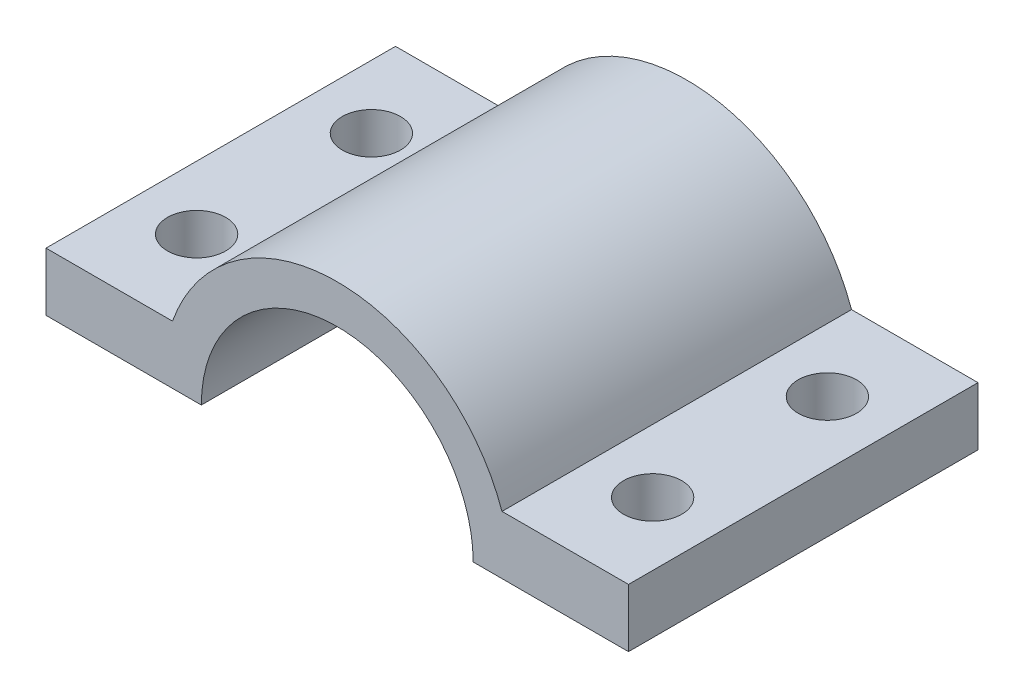
SolidWorks part; units mm, degrees
ref_plane "前视基准面" through (0, 0, 0) normal (0, 0, 1) x (1, 0, 0)
ref_plane "上视基准面" through (0, 0, 0) normal (0, 1, 0) x (1, 0, 0)
ref_plane "右视基准面" through (0, 0, 0) normal (1, 0, 0) x (0, 0, -1)
sketch "草图1" plane through (0, 0, 0) normal (0, 0, 1) x (1, 0, 0)
  line L0 (0, 0) -> (8, 0)
  line L1 (30, 0) -> (30, 3)
  line L2 (30, 3) -> (23.4853, 3)
  line L3 (0, 3) -> (0, 0)
  line L4 (6.5147, 3) -> (0, 3)
  line L5 (22, 0) -> (30, 0)
  arc A0 (23.4853, 3) -> (6.5147, 3) centre (15, 0) ccw
  arc A1 (22, 0) -> (8, 0) centre (15, 0) ccw
  dimension "D1" = 30
  dimension "D3" = 14
  dimension "D4" = 18
  dimension "D2" = 3
extrude "凸台-拉伸1" add sketch "草图1" along normal blind 18
ref_plane "基准面2" through (0, 4, 0) normal (0, 1, 0) x (1, 0, 0)
sketch "草图3" plane through (0, 4, 0) normal (0, 1, 0) x (1, 0, 0)
  circle A1 centre (15, -7.5) radius 3.5
  dimension "D1" = 7
extrude "凸台-拉伸2" add sketch "草图3" along normal up to next
sketch "草图4" plane through (0, 3, 0) normal (0, 1, 0) x (1, 0, 0)
  line L0 (3.2574, 0) -> (3.2574, -18)
  line L1 (6.5147, 0) -> (0, 0) construction
  line L2 (6.5147, -18) -> (0, -18) construction
  line L3 (26.7426, 0) -> (26.7426, -18)
  line L4 (30, 0) -> (23.4853, 0) construction
  line L5 (30, -18) -> (23.4853, -18) construction
  line L7 (-4.95, 0) -> (4.95, 0) construction
  circle A0 centre (3.2574, -4.5) radius 1.5
  circle A1 centre (3.2574, -13.5) radius 1.5
  circle A2 centre (26.7426, -4.5) radius 1.5
  circle A3 centre (26.7426, -13.5) radius 1.5
  point P6 (3.2574, -4.5)
  point P7 (3.2574, -13.5)
  point P12 (26.7426, -4.5)
  point P19 (26.7426, -13.5)
  dimension "D3" = 4.5
  dimension "D1" = 4.5
  dimension "D2" = 4.5
  dimension "D4" = 4.5
extrude "切除-拉伸1" cut sketch "草图4" against normal blind 3 contours L0 A0 | L0 A0 | L0 A1 | L0 A1 | L3 A2 | L3 A2 | L3 A3 | L3 A3
